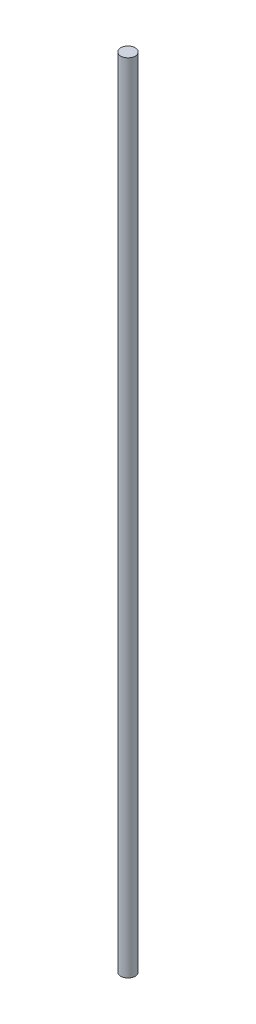
SolidWorks part; units mm, degrees
ref_plane "Front Plane" through (0, 0, 0) normal (0, 0, 1) x (1, 0, 0)
ref_plane "Top Plane" through (0, 0, 0) normal (0, 1, 0) x (1, 0, 0)
ref_plane "Right Plane" through (0, 0, 0) normal (1, 0, 0) x (0, 0, -1)
sketch "Sketch1" plane through (0, 0, 0) normal (0, 1, 0) x (1, 0, 0)
  circle A0 centre (0, 0) radius 2
extrude "Boss-Extrude1" add sketch "Sketch1" along normal blind 220
